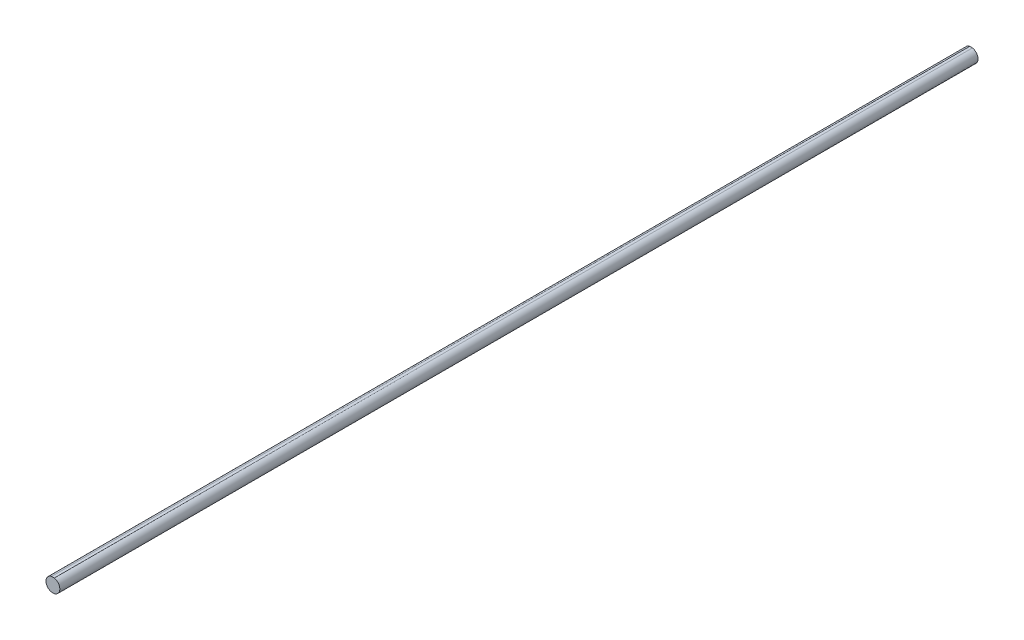
SolidWorks part; units mm, degrees
ref_plane "Спереди" through (0, 0, 0) normal (0, 0, 1) x (1, 0, 0)
ref_plane "Сверху" through (0, 0, 0) normal (0, 1, 0) x (1, 0, 0)
ref_plane "Справа" through (0, 0, 0) normal (1, 0, 0) x (0, 0, -1)
sketch "Эскиз1" plane through (0, 0, 0) normal (0, 0, 1) x (1, 0, 0)
  circle A0 centre (0, 0) radius 5
  dimension "D1" = 10
extrude "Бобышка-Вытянуть1" add sketch "Эскиз1" against normal blind 665
sketch "Эскиз2" plane through (0, 0, 0) normal (0, 0, 1) x (1, 0, 0)
  line L0 (0, 0) -> (0, 5)
  line L1 (0, 5) -> (0, 4.9)
  line L2 (0, 4.9) -> (-2.3504, 4.9)
  line L3 (-2.3504, 4.9) -> (-2.3504, 5.6447)
  line L4 (-2.3504, 5.6447) -> (3.1437, 5.6447)
  line L5 (3.1437, 5.6447) -> (3.1437, 4.9)
  line L6 (3.1437, 4.9) -> (0, 4.9)
  circle A0 centre (0, 0) radius 5 construction
  circle M1 centre (0, 0) radius 5
  dimension "D1" = 0.1
extrude "Вырез-Вытянуть1" cut sketch "Эскиз2" against normal through all contours L6 L0 M1 | L2 L0 M1
